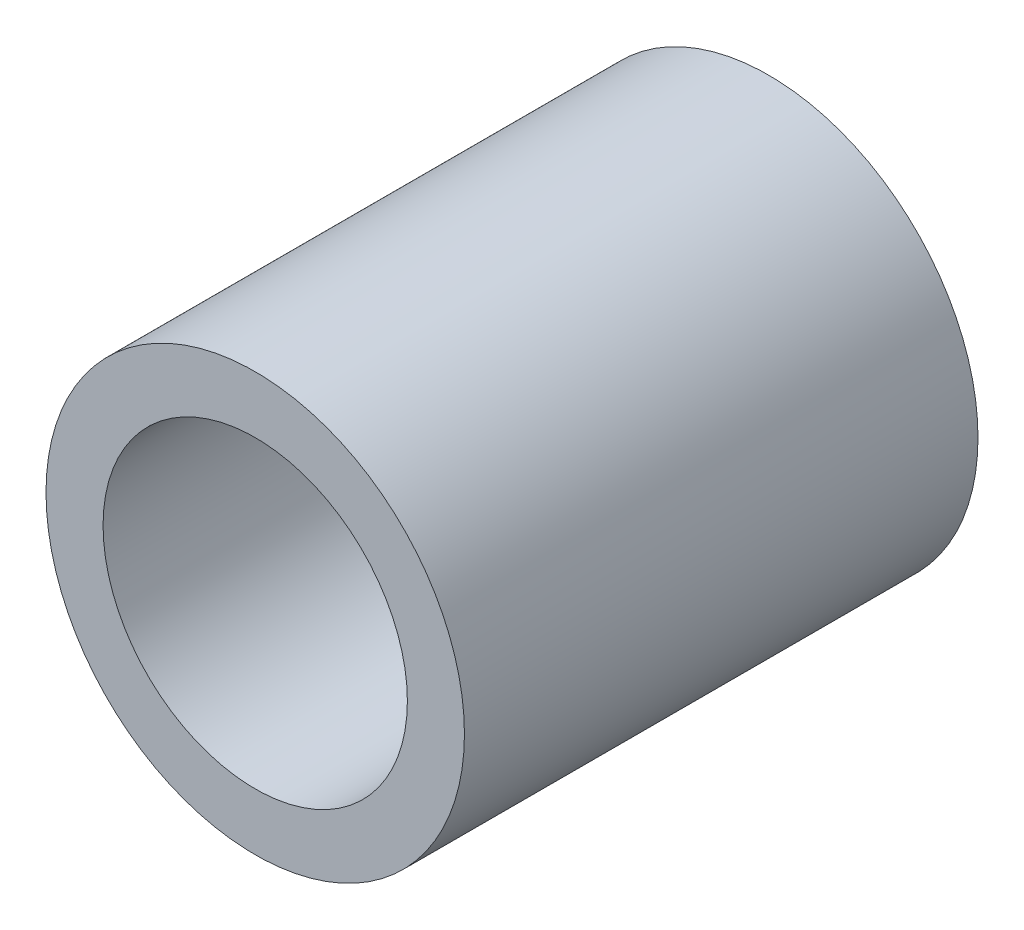
SolidWorks part; units mm, degrees
ref_plane "Alzado" through (0, 0, 0) normal (0, 0, 1) x (1, 0, 0)
ref_plane "Planta" through (0, 0, 0) normal (0, 1, 0) x (1, 0, 0)
ref_plane "Vista lateral" through (0, 0, 0) normal (1, 0, 0) x (0, 0, -1)
sketch "Croquis1" plane through (0, 0, 0) normal (0, 0, 1) x (1, 0, 0)
  circle A0 centre (0, 0) radius 8
  circle A1 centre (0, 0) radius 11
  dimension "D1" = 16
  dimension "D2" = 22
extrude "Saliente-Extruir1" add sketch "Croquis1" against normal blind 27
